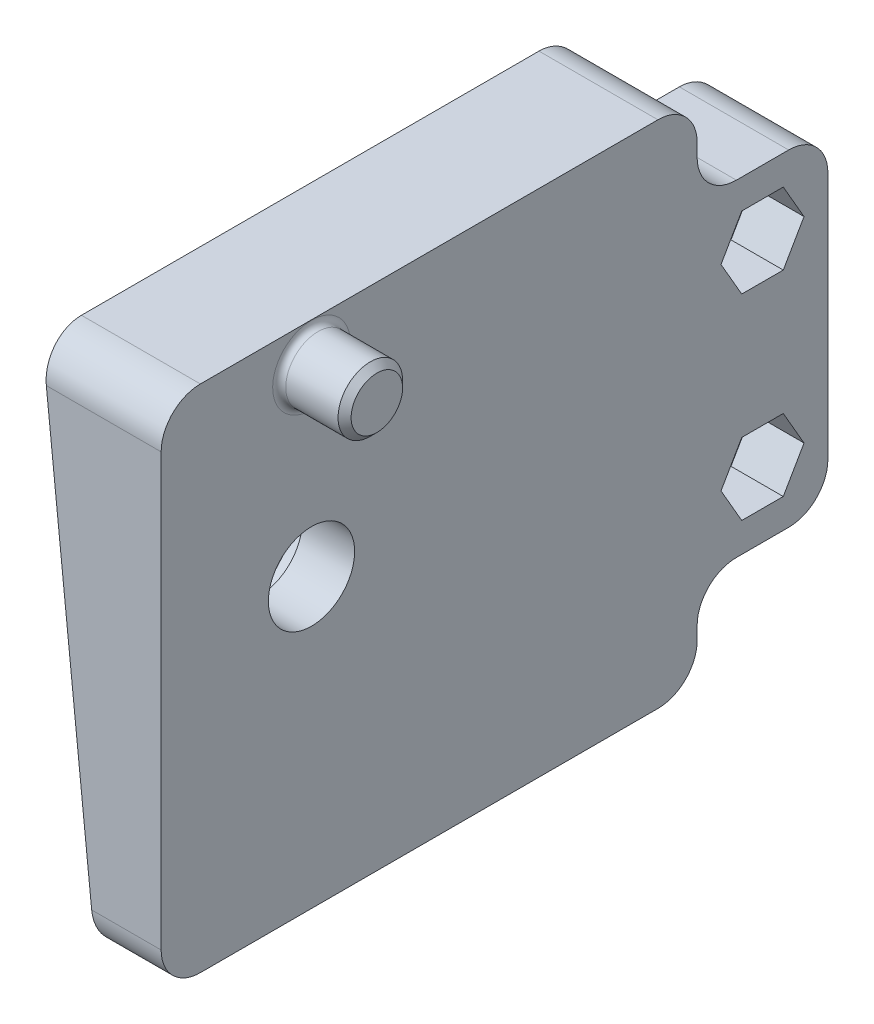
SolidWorks part; units mm, degrees
ref_plane "前视基准面" through (0, 0, 0) normal (0, 0, 1) x (1, 0, 0)
ref_plane "上视基准面" through (0, 0, 0) normal (0, 1, 0) x (1, 0, 0)
ref_plane "右视基准面" through (0, 0, 0) normal (1, 0, 0) x (0, 0, -1)
other "Configuration Table"
sketch "草图1" plane through (0, 0, 0) normal (0, 0, 1) x (1, 0, 0)
  line L0 (0, 0) -> (5, 0)
  line L1 (0, 0) -> (-4.0991, 39)
  line L2 (-4.0991, 39) -> (5, 39)
  line L3 (5, 39) -> (5, 0)
  dimension "D1" = 5
  dimension "D2" = 39
  dimension "D3" = 6
extrude "凸台-拉伸1" add sketch "草图1" along normal blind 41
sketch "草图2" plane through (5, 0, 0) normal (1, 0, 0) x (0, 0, -1)
  line L0 (-41, 39) -> (0, 39) construction
  circle A0 centre (-29.5, 22) radius 3.3
  point P2 (-20.5, 39)
  point P3 (0, 0)
  point P6 (0, 0)
  point P7 (-24.781, 22.5479)
  dimension "D1" = 9
  dimension "D2" = 6.6
  dimension "D3" = 17
extrude "切除-拉伸1" cut sketch "草图2" against normal up to surface (7.6591 mm away)
ref_plane "基准面2" through (1, 0, 0) normal (-1, 0, 0) x (0, 0, 1)
sketch "草图3" plane through (1, 0, 0) normal (-1, 0, 0) x (0, 0, 1)
  circle A0 centre (29.5, 22) radius 6.4
extrude "切除-拉伸2" cut sketch "草图3" along normal up to surface (2.6396 mm away)
sketch "草图4" plane through (5, 0, 0) normal (1, 0, 0) x (0, 0, -1)
  line L0 (-41, 39) -> (0, 39) construction
  circle A0 centre (-29.5, 36) radius 2.47
  point P0 (-20.5, 39)
  point P5 (0, 0)
  point P6 (-22.2759, 36.5821)
  dimension "D1" = 4.94
  dimension "D2" = 3
  dimension "D3" = 9
extrude "凸台-拉伸2" add sketch "草图4" along normal blind 5
chamfer "倒角1" distance 0.5 angle 45 1 edges at (10, 38.47, 29.5)
fillet "圆角1" radius 0.5 1 edges at (5, 33.53, 29.5)
sketch "草图5" plane through (0, 0, 0) normal (0, 0, -1) x (-1, 0, 0)
  line L0 (-5, 32) -> (3.3633, 32)
  line L1 (-5, 7) -> (0.7357, 7)
  line L2 (-5, 39) -> (4.0991, 39) construction
  line L3 (-5, 32) -> (-5, 7)
  line L4 (-5, 0) -> (-5, 39) construction
  line L5 (3.3633, 32) -> (0.7357, 7)
  line L6 (4.0991, 39) -> (0, 0) construction
  dimension "D1" = 7
  dimension "D2" = 32
extrude "凸台-拉伸3" add sketch "草图5" along normal blind 10
sketch "草图6" plane through (5, 0, 0) normal (1, 0, 0) x (0, 0, -1)
  line L0 (10, 32) -> (10, 7) construction
  line L1 (8.1754, 27) -> (6.5877, 29.75)
  line L2 (6.5877, 29.75) -> (3.4123, 29.75)
  line L3 (3.4123, 29.75) -> (1.8246, 27)
  line L4 (1.8246, 27) -> (3.4123, 24.25)
  line L5 (3.4123, 24.25) -> (6.5877, 24.25)
  line L6 (6.5877, 24.25) -> (8.1754, 27)
  line L7 (8.1754, 12) -> (6.5877, 14.75)
  line L8 (6.5877, 14.75) -> (3.4123, 14.75)
  line L9 (3.4123, 14.75) -> (1.8246, 12)
  line L10 (1.8246, 12) -> (3.4123, 9.25)
  line L11 (3.4123, 9.25) -> (6.5877, 9.25)
  line L12 (6.5877, 9.25) -> (8.1754, 12)
  line L13 (10, 32) -> (0, 32) construction
  line L14 (10, 7) -> (0, 7) construction
  circle A0 centre (5, 27) radius 2.75 construction
  circle A1 centre (5, 12) radius 2.75 construction
  dimension "D5" = 5.5
  dimension "D6" = 5.5
  dimension "D1" = 5
  dimension "D2" = 5
  dimension "D3" = 5
  dimension "D4" = 5
extrude "切除-拉伸3" cut sketch "草图6" against normal blind 4
sketch "草图7" plane through (1, 0, 0) normal (1, 0, 0) x (0, 0, -1)
  circle A0 centre (5, 27) radius 1.65
  circle A1 centre (5, 12) radius 1.65
  dimension "D1" = 3.3
  dimension "D2" = 3.3
extrude "切除-拉伸4" cut sketch "草图7" against normal up to surface (3.8378 mm away)
fillet "圆角2" radius 3 8 edges at (0.4505, 39, 41) (2.5, 0, 41) (2.5, 0, 0) (2.1321, 7, 0) (2.1321, 7, -10) (0.8183, 32, -10) (0.8183, 32, 0) (0.4505, 39, 0)
